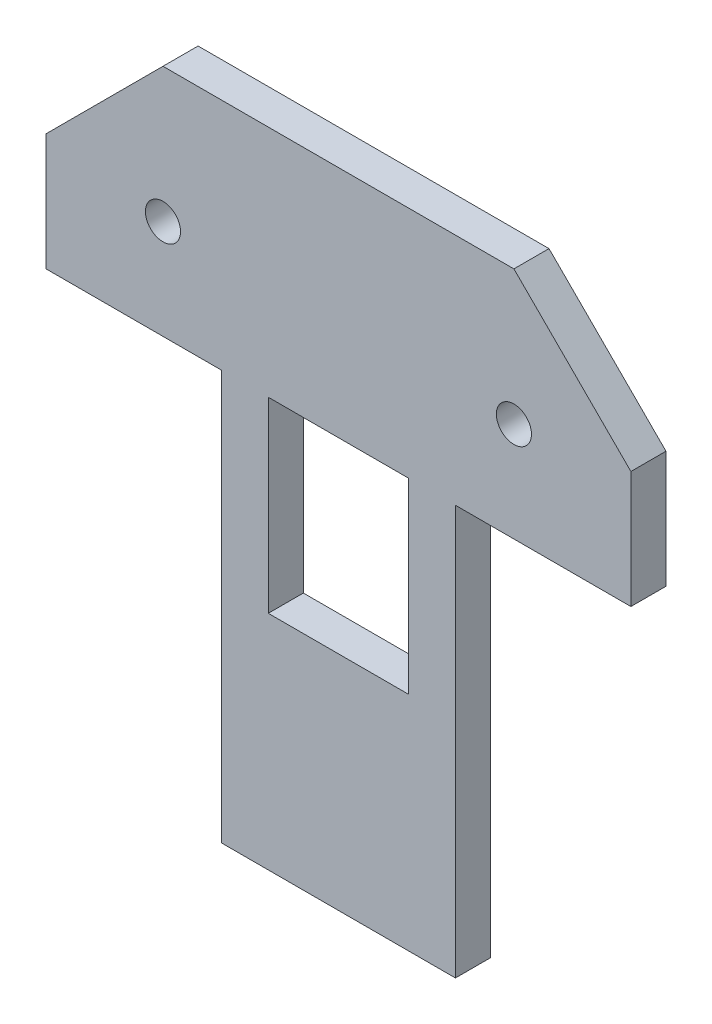
SolidWorks part; units mm, degrees
ref_plane "Alzado" through (0, 0, 0) normal (0, 0, 1) x (1, 0, 0)
ref_plane "Planta" through (0, 0, 0) normal (0, 1, 0) x (1, 0, 0)
ref_plane "Vista lateral" through (0, 0, 0) normal (1, 0, 0) x (0, 0, -1)
sketch "Croquis1" plane through (0, 0, 0) normal (0, 0, 1) x (1, 0, 0)
  line L0 (-25, 0) -> (-15, 10)
  line L1 (-25, -10) -> (-10, -10)
  line L2 (-25, -10) -> (-25, 0)
  line L3 (-15, 10) -> (15, 10)
  line L4 (25, -10) -> (25, 0)
  line L5 (-25, -10) -> (25, 10) construction
  line L6 (-25, 10) -> (25, -10) construction
  line L7 (15, 10) -> (25, 0)
  line L8 (-15, 10) -> (-15, -1.5) construction
  line L9 (-15, -1.5) -> (15, -1.5) construction
  line L10 (15, -1.5) -> (15, 10) construction
  line L11 (0, 0) -> (-10, 0) construction
  line L12 (10, -10) -> (25, -10)
  line L13 (10, -10) -> (-10, -10) construction
  line L14 (-10, -10) -> (-10, -45)
  line L15 (-10, -45) -> (10, -45)
  line L16 (10, -10) -> (10, -45)
  line L17 (-6, -10) -> (6, -10)
  line L18 (-6, -10) -> (-6, -26)
  line L19 (-6, -26) -> (6, -26)
  line L20 (6, -10) -> (6, -26)
  circle A0 centre (-15, -1.5) radius 1.5
  circle A1 centre (15, -1.5) radius 1.5
  point P0 (0, 0)
  dimension "D1" = 20
  dimension "D2" = 50
  dimension "D3" = 20
  dimension "D4" = 35
  dimension "D5" = 16
  dimension "D8" = 12
  dimension "D9" = 4
  dimension "D10" = 15
extrude "Saliente-Extruir1" add sketch "Croquis1" along normal blind 3
